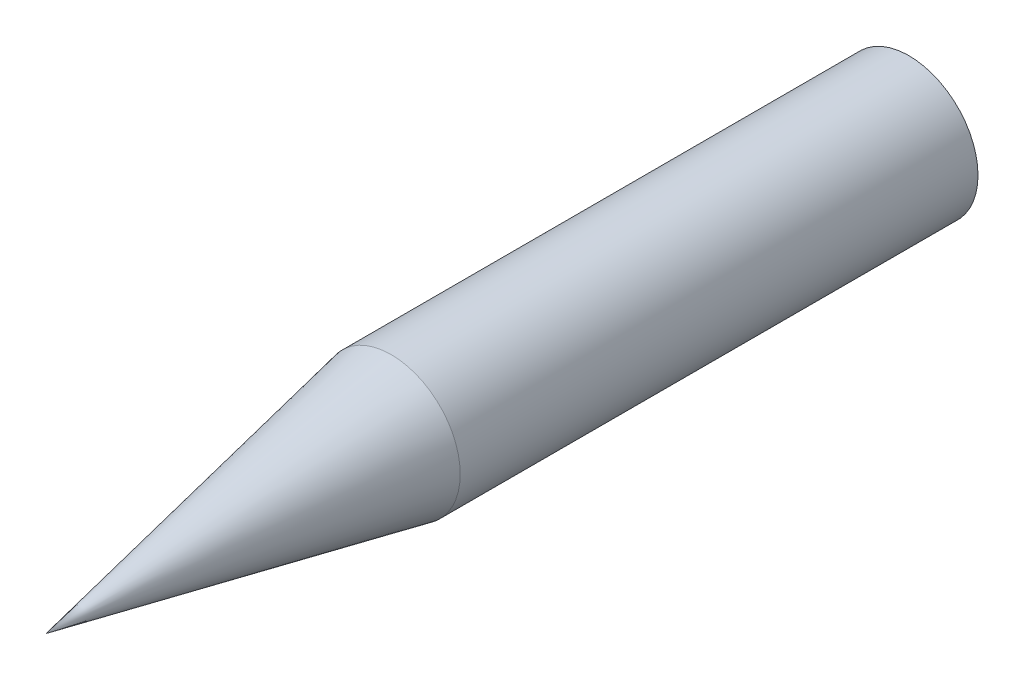
SolidWorks part; units mm, degrees
ref_plane "Front Plane" through (0, 0, 0) normal (0, 0, 1) x (1, 0, 0)
ref_plane "Top Plane" through (0, 0, 0) normal (0, 1, 0) x (1, 0, 0)
ref_plane "Right Plane" through (0, 0, 0) normal (1, 0, 0) x (0, 0, -1)
sketch "Sketch1" plane through (0, 0, 0) normal (0, 0, 1) x (1, 0, 0)
  circle A0 centre (0, 0) radius 4
  dimension "D1" = 8
extrude "Boss-Extrude1" add sketch "Sketch1" along normal blind 50
chamfer "Chamfer1" distance 20 distance2 4 1 edges at (4, 0, 50)
